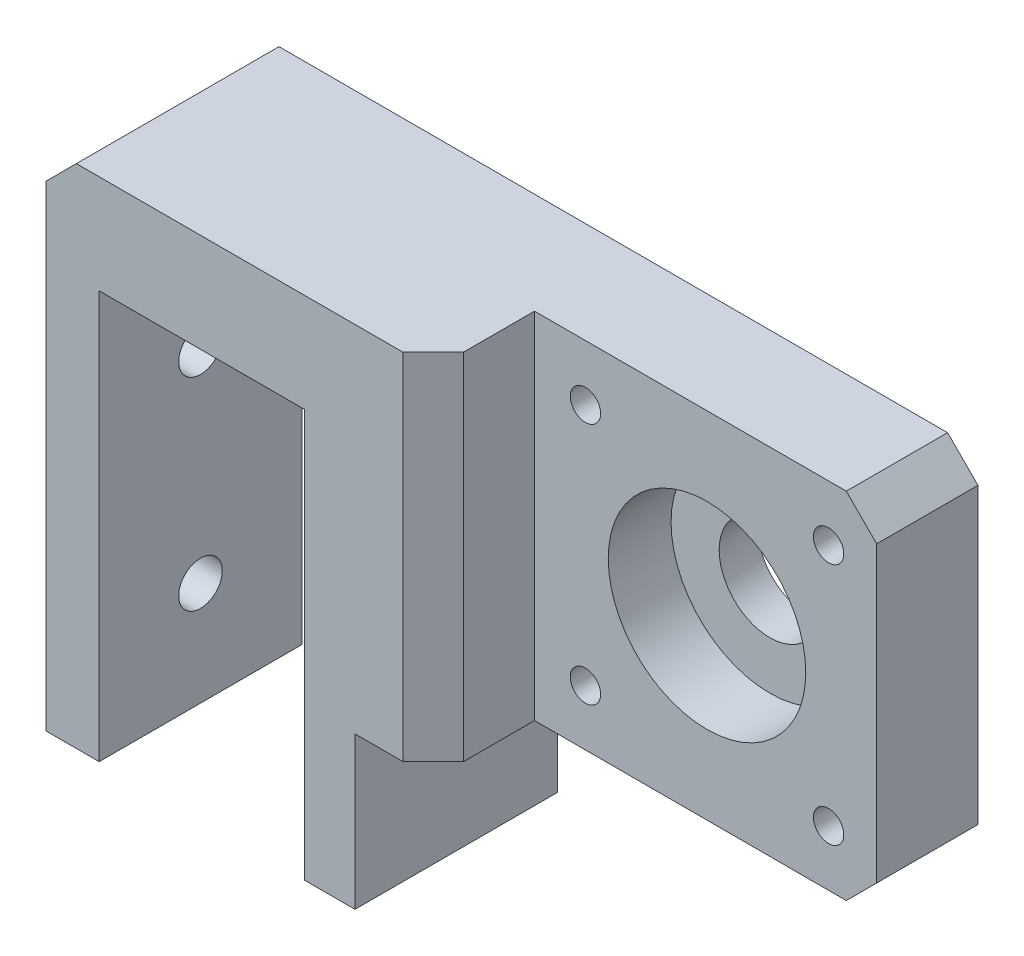
SolidWorks part; units mm, degrees
ref_plane "前视基准面" through (0, 0, 0) normal (0, 0, 1) x (1, 0, 0)
ref_plane "上视基准面" through (0, 0, 0) normal (0, 1, 0) x (1, 0, 0)
ref_plane "右视基准面" through (0, 0, 0) normal (1, 0, 0) x (0, 0, -1)
sketch "草图5" plane through (0, 0, 0) normal (0, 0, 1) x (1, 0, 0)
  line L0 (0, 0) -> (0, 50)
  line L1 (0, 50) -> (72, 50)
  line L2 (72, 50) -> (72, 15)
  line L3 (72, 15) -> (30.5, 15)
  line L4 (30.5, 15) -> (30.5, 0)
  line L5 (30.5, 0) -> (25.5, 0)
  line L6 (5, 0) -> (5, 40.5)
  line L7 (5, 40.5) -> (25.5, 40.5)
  line L8 (25.5, 40.5) -> (25.5, 0)
  line L9 (5, 0) -> (0, 0)
  circle A0 centre (55.25, 32.5) radius 5
  circle A1 centre (43.25, 44.5) radius 1.5
  circle A2 centre (67.25, 44.5) radius 1.5
  circle A3 centre (43.25, 20.5) radius 1.5
  circle A4 centre (67.25, 20.5) radius 1.5
  dimension "D10" = 10
  dimension "D15" = 3
  dimension "D1" = 50
  dimension "D2" = 40.5
  dimension "D3" = 20.5
  dimension "D4" = 5
  dimension "D5" = 5
  dimension "D6" = 72
  dimension "D7" = 35
  dimension "D8" = 16.75
  dimension "D9" = 17.5
  dimension "D11" = 12
  dimension "D12" = 12
  dimension "D13" = 12
  dimension "D14" = 12
extrude "凸台-拉伸1" add sketch "草图5" along normal blind 20
sketch "草图6" plane through (0, 0, 0) normal (-1, 0, 0) x (0, 0, 1)
  line L1 (20, 0) -> (0, 0) construction
  line L2 (20, 50) -> (20, 0) construction
  circle A0 centre (10, 10.25) radius 2.15
  circle A1 centre (10, 30.25) radius 2.15
  dimension "D4" = 4.3
  dimension "D1" = 20
  dimension "D2" = 10.25
  dimension "D3" = 10
extrude "切除-拉伸3" cut sketch "草图6" against normal blind 20
sketch "草图7" plane through (30.5, 0, 0) normal (1, 0, 0) x (0, 0, -1)
  circle A0 centre (-10, 10.25) radius 2.15 construction
  circle A1 centre (-10, 10.25) radius 2.15
extrude "切除-拉伸4" cut sketch "草图7" against normal blind 20
sketch "草图8" plane through (0, 0, 0) normal (0, 0, -1) x (-1, 0, 0)
  line L0 (-30.5, 15) -> (-72, 15) construction
  line L1 (-72, 50) -> (-38.2227, 50)
  line L2 (-72, 50) -> (-72, 15)
  line L3 (-72, 15) -> (-38.2227, 15)
  line L4 (-38.2227, 50) -> (-38.2227, 15)
extrude "切除-拉伸5" cut sketch "草图8" against normal blind 10
sketch "草图9" plane through (0, 0, 10) normal (0, 0, -1) x (-1, 0, 0)
  circle A0 centre (-55.25, 32.5) radius 9.75
  dimension "D1" = 19.5
extrude "切除-拉伸6" cut sketch "草图9" against normal blind 6.2
chamfer "倒角1" distance 3 angle 45 4 edges at (0, 50, 10) (38.2227, 32.5, 0) (72, 15, 15) (72, 50, 15)
mirror "镜向1" about plane through (0, 0, 20) normal (0, 0, -1) of bodies 114 115
sketch "草图12" plane through (0, 0, 0) normal (0, 0, -1) x (-1, 0, 0)
  line L1 (-86.3012, 61.5454) -> (24.1069, 61.5454)
  line L2 (-86.3012, 61.5454) -> (-86.3012, -11.7581)
  line L3 (-86.3012, -11.7581) -> (24.1069, -11.7581)
  line L4 (24.1069, 61.5454) -> (24.1069, -11.7581)
extrude "切除-拉伸8" cut sketch "草图12" against normal up to vertex (20 mm away) up to point (0, 47, 20)
sketch "草图13" plane through (0, 40.5, 0) normal (0, -1, 0) x (1, 0, 0)
  line L4 (25.5, 40) -> (5, 40)
  line L5 (5, 40) -> (5, 20)
  line L6 (5, 20) -> (25.5, 20)
  line L7 (25.5, 20) -> (25.5, 40)
  line L8 (25.5, 40) -> (5, 40)
  line L9 (5, 40) -> (5, 20)
  line L10 (5, 20) -> (25.5, 20)
  line L11 (25.5, 20) -> (25.5, 40)
  dimension "D1" = 0
extrude "凸台-拉伸2" add sketch "草图13" along normal blind 0.25
sketch "草图14" plane through (5, 0, 0) normal (1, 0, 0) x (0, 0, -1)
  line L4 (-20, 0) -> (-20, 40.25)
  line L5 (-20, 40.25) -> (-40, 40.25)
  line L6 (-40, 40.25) -> (-40, 0)
  line L7 (-40, 0) -> (-20, 0)
  line L8 (-20, 0) -> (-20, 40.25)
  line L9 (-20, 40.25) -> (-40, 40.25)
  line L10 (-40, 40.25) -> (-40, 0)
  line L11 (-40, 0) -> (-20, 0)
  circle A0 centre (-30, 10.25) radius 2.15 construction
  circle A1 centre (-30, 30.25) radius 2.15 construction
  circle A2 centre (-30, 10.25) radius 2.15
  circle A3 centre (-30, 30.25) radius 2.15
  dimension "D1" = 0
extrude "凸台-拉伸3" add sketch "草图14" along normal blind 0.25
